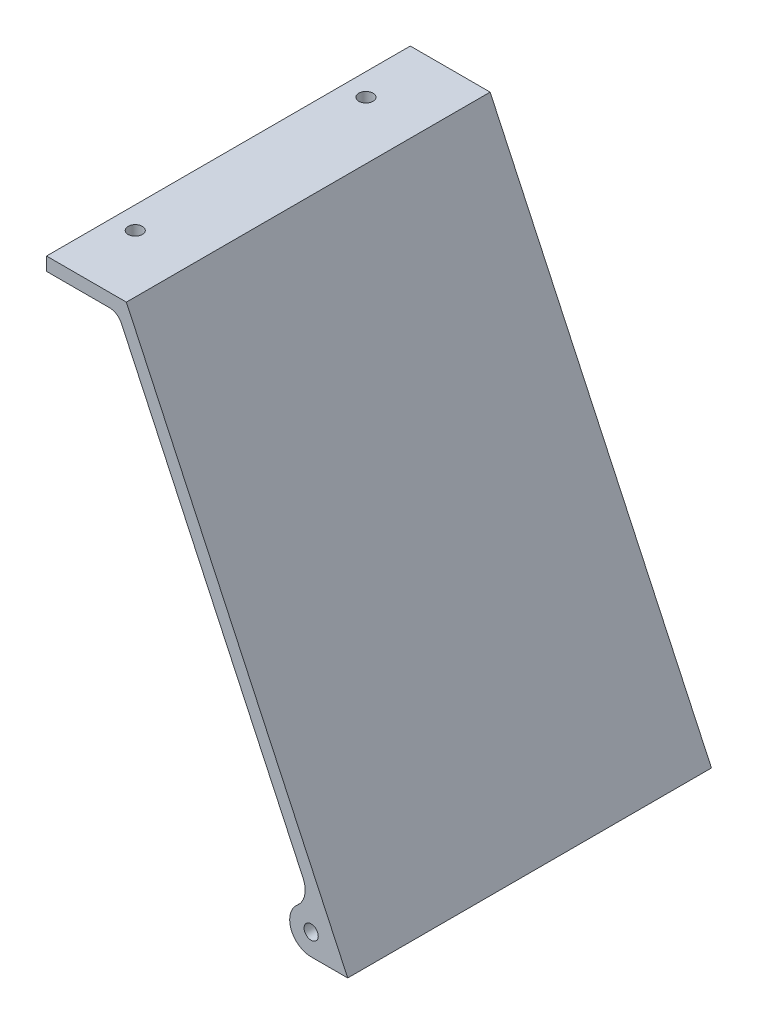
SolidWorks part; units mm, degrees
material "ABS"
ref_plane "前视基准面" through (0, 0, 0) normal (0, 0, 1) x (1, 0, 0)
ref_plane "上视基准面" through (0, 0, 0) normal (0, 1, 0) x (1, 0, 0)
ref_plane "右视基准面" through (0, 0, 0) normal (1, 0, 0) x (0, 0, -1)
sketch "草图1" plane through (0, 0, 0) normal (0, 0, 1) x (1, 0, 0)
  line L0 (25.7263, -61.5436) -> (30.5797, -71.9517)
  line L1 (-34.0772, 35.2031) -> (-16.0772, 35.2031)
  line L2 (-17.9884, 32.2031) -> (25.7263, -61.5436)
  line L3 (-16.0772, 35.2031) -> (33.8899, -71.9517)
  line L5 (-34.0772, 35.2031) -> (-34.0772, 32.2031)
  line L6 (-34.0772, 32.2031) -> (-17.9884, 32.2031)
  line L7 (33.8899, -71.9517) -> (30.5797, -71.9517)
extrude "凸台-拉伸1" add sketch "草图1" along normal blind 82
sketch "草图2" plane through (0, 0, 0) normal (0, 0, -1) x (-1, 0, 0)
  line L0 (-30.5797, -71.9517) -> (-25.5797, -71.9517)
  line L6 (-23.6886, -57.1737) -> (-30.5797, -71.9517)
  arc A0 (-25.5797, -71.9517) -> (-22.3684, -63.1193) centre (-25.5797, -66.9517) ccw
  arc A1 (-22.3684, -63.1193) -> (-23.6886, -57.1737) centre (-19.1571, -59.2868) cw
  circle A2 centre (-25.5797, -66.9517) radius 1.6
  dimension "D1" = 5
  dimension "D2" = 3.2
  dimension "D3" = 5
sketch "草图4" plane through (0, 32.2031, 0) normal (0, -1, 0) x (1, 0, 0)
  line L0 (-34.0772, 82) -> (-17.9884, 82) construction
  line L1 (-34.0772, 82) -> (-34.0772, 0) construction
  line L2 (-17.9884, 41) -> (10.6682, 41) construction
  line L3 (-17.9884, 82) -> (-17.9884, 0) construction
  circle A0 centre (-29.0772, 67) radius 1.6
  circle A1 centre (-29.0772, 15) radius 1.6
  dimension "D3" = 3.2
  dimension "D1" = 15
  dimension "D2" = 5
extrude "切除-拉伸1" cut sketch "草图4" against normal blind 10
fillet "圆角1" radius 3 1 edges at (-17.9884, 32.2031, 41)
sketch "草图5" plane through (0, 0, 0) normal (0, 0, -1) x (-1, 0, 0)
  line L1 (-25.5797, -71.7969) -> (-30.5076, -71.7969)
  line L3 (-23.7564, -57.319) -> (-30.5076, -71.7969)
  arc A0 (-25.5797, -71.7969) -> (-22.4522, -63.251) centre (-25.5797, -66.9517) ccw
  circle A1 centre (-25.5797, -66.9517) radius 1.6
  arc A2 (-22.4522, -63.251) -> (-23.7564, -57.319) centre (-19.2248, -59.4321) cw
  dimension "D2" = 5
  dimension "D1" = 104
extrude "凸台-拉伸2" add sketch "草图5" against normal blind 5
sketch "草图6" plane through (0, 0, 82) normal (0, 0, 1) x (1, 0, 0)
  line L2 (25.5797, -71.7969) -> (30.5076, -71.7969)
  line L3 (23.7564, -57.319) -> (30.5076, -71.7969)
  circle A0 centre (25.5797, -66.9517) radius 1.6
  arc A1 (22.4522, -63.251) -> (25.5797, -71.7969) centre (25.5797, -66.9517) ccw
  arc A2 (22.4522, -63.251) -> (23.7564, -57.319) centre (19.2248, -59.4321) ccw
  dimension "D1" = 5
extrude "凸台-拉伸3" add sketch "草图6" against normal blind 5
sketch "草图7" plane through (0, 0, 82) normal (0, 0, 1) x (1, 0, 0)
  line L0 (30.5076, -71.7969) -> (36.4536, -71.7969)
  line L1 (36.4536, -71.7969) -> (36.4536, -72.6703)
  line L2 (36.4536, -72.6703) -> (30.5076, -72.6703)
  line L3 (30.5076, -72.6703) -> (30.5076, -71.7969)
extrude "切除-拉伸2" cut sketch "草图7" against normal through all
